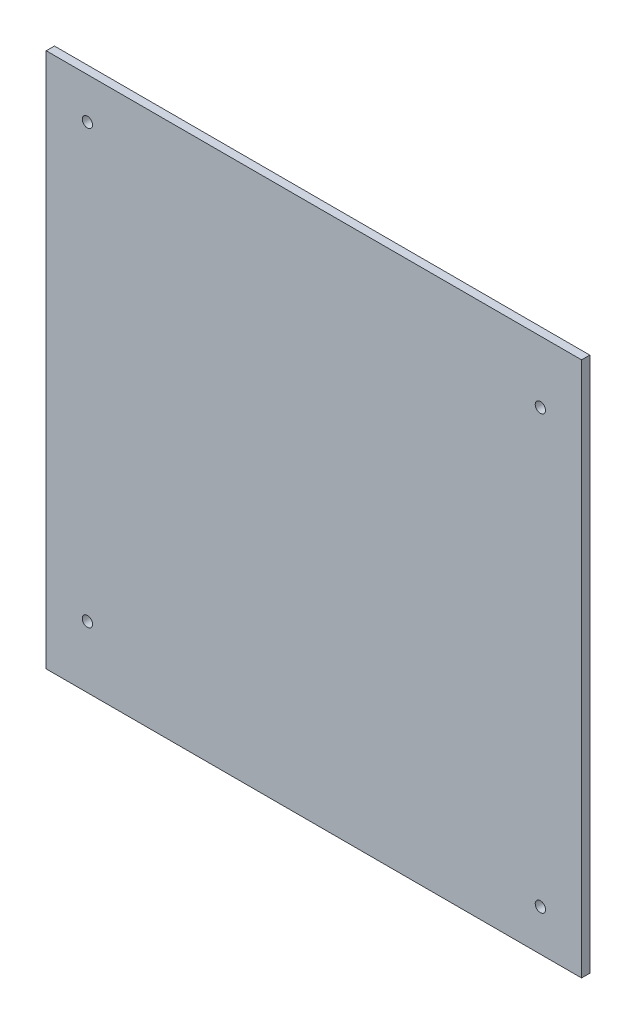
SolidWorks part; units mm, degrees
ref_plane "Спереди" through (0, 0, 0) normal (0, 0, 1) x (1, 0, 0)
ref_plane "Сверху" through (0, 0, 0) normal (0, 1, 0) x (1, 0, 0)
ref_plane "Справа" through (0, 0, 0) normal (1, 0, 0) x (0, 0, -1)
sketch "Эскиз1" plane through (0, 0, 0) normal (0, 0, 1) x (1, 0, 0)
  line L1 (-65, -65) -> (65, -65)
  line L2 (-65, -65) -> (-65, 65)
  line L3 (-65, 65) -> (65, 65)
  line L4 (65, -65) -> (65, 65)
  line L5 (-65, -65) -> (65, 65) construction
  line L6 (-65, 65) -> (65, -65) construction
  circle A0 centre (-55, 55) radius 1.25
  circle A1 centre (55, 50) radius 1.25
  circle A2 centre (55, -55) radius 1.25
  circle A3 centre (-55, -50) radius 1.25
  point P0 (0, 0)
  dimension "D3" = 2.5
  dimension "D4" = 2.5
  dimension "D5" = 2.5
  dimension "D6" = 2.5
  dimension "D8" = 10
  dimension "D9" = 10
  dimension "D11" = 10
  dimension "D12" = 10
  dimension "D13" = 10
  dimension "D14" = 15
  dimension "D1" = 130
  dimension "D2" = 130
  dimension "D7" = 10
  dimension "D10" = 15
extrude "Бобышка-Вытянуть1" add sketch "Эскиз1" along normal blind 2
